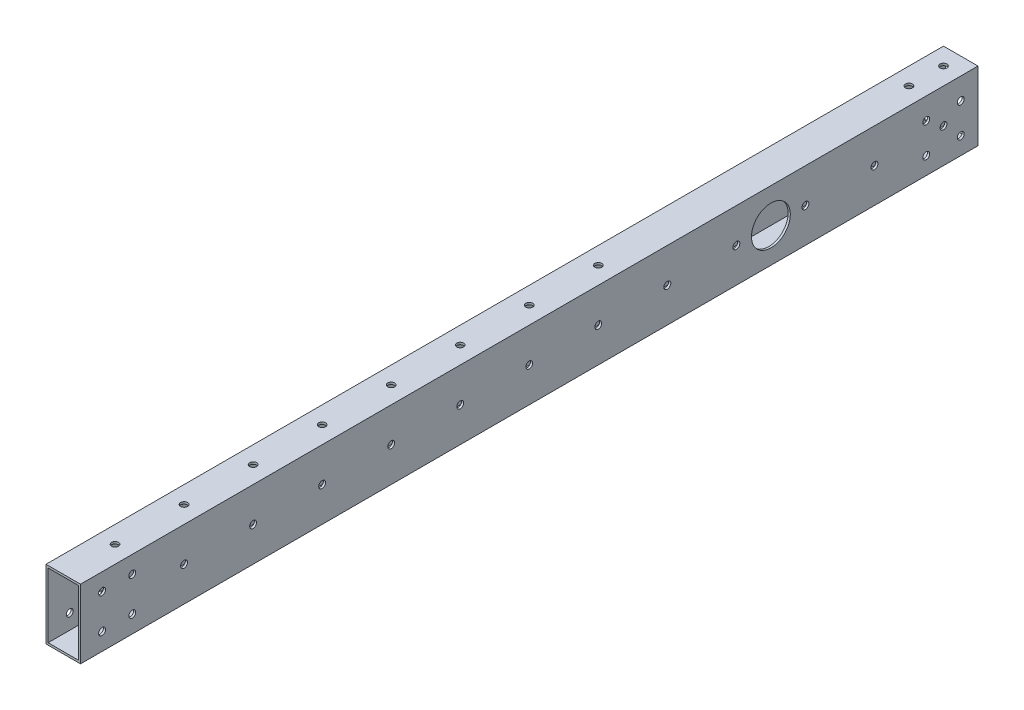
SolidWorks part; units mm, degrees
ref_plane "Front Plane" through (0, 0, 0) normal (0, 0, 1) x (1, 0, 0)
ref_plane "Top Plane" through (0, 0, 0) normal (0, 1, 0) x (1, 0, 0)
ref_plane "Right Plane" through (0, 0, 0) normal (1, 0, 0) x (0, 0, -1)
sketch "Sketch1" plane through (0, 0, 0) normal (0, 0, 1) x (1, 0, 0)
  line L0 (-11.1125, -23.8125) -> (11.1125, 23.8125) construction
  line L1 (-12.7, -25.4) -> (12.7, -25.4)
  line L2 (-12.7, -25.4) -> (-12.7, 25.4)
  line L3 (-12.7, 25.4) -> (12.7, 25.4)
  line L4 (12.7, -25.4) -> (12.7, 25.4)
  line L5 (-11.1125, -23.8125) -> (11.1125, -23.8125)
  line L6 (-11.1125, -23.8125) -> (-11.1125, 23.8125)
  line L7 (-11.1125, 23.8125) -> (11.1125, 23.8125)
  line L8 (11.1125, -23.8125) -> (11.1125, 23.8125)
  dimension "D1" = 25.4
  dimension "D2" = 50.8
  dimension "D3" = 1.5875
  dimension "D4" = 1.5875
  dimension "D5" = 1.5875
  dimension ".0625" = 1.5875
extrude "Boss-Extrude1" add sketch "Sketch1" along normal blind 660.4
sketch "Sketch2" plane through (12.7, 0, 0) normal (1, 0, 0) x (0, 0, -1)
  line L0 (-644.525, -12.7) -> (-660.4, 0) construction
  line L1 (-660.4, 25.4) -> (0, 25.4) construction
  line L2 (-660.4, -25.4) -> (0, -25.4) construction
  line L3 (0, -25.4) -> (0, 25.4) construction
  line L4 (-660.4, 0) -> (-644.525, 12.7) construction
  line L5 (-660.4, -25.4) -> (-660.4, 25.4) construction
  circle A0 centre (-38.1, 9.525) radius 2.54
  circle A1 centre (-38.1, -12.7) radius 2.54
  circle A2 centre (-12.7, 9.525) radius 2.54
  circle A3 centre (-12.7, -12.7) radius 2.54
  circle A4 centre (-152.4, 0) radius 14.2875
  circle A5 centre (-644.525, -12.7) radius 2.54
  circle A6 centre (-622.3, -12.7) radius 2.54
  circle A7 centre (-644.525, 12.7) radius 2.54
  circle A8 centre (-622.3, 12.7) radius 2.54
  circle A9 centre (-25.4, 0) radius 2.54
  circle A20 centre (-76.2, 0) radius 2.54
  circle A21 centre (-127, 0) radius 2.54
  circle A22 centre (-177.8, 0) radius 2.54
  circle A23 centre (-228.6, 0) radius 2.54
  circle A24 centre (-279.4, 0) radius 2.54
  circle A25 centre (-330.2, 0) radius 2.54
  circle A26 centre (-381, 0) radius 2.54
  circle A27 centre (-431.8, 0) radius 2.54
  circle A28 centre (-482.6, 0) radius 2.54
  circle A29 centre (-533.4, 0) radius 2.54
  circle A30 centre (-584.2, 0) radius 2.54
  point P28 (0, 0)
  dimension "D1" = 5.08
  dimension "D6" = 28.575
  dimension "D12" = 5.08
  dimension "D2" = 25.4
  dimension "D3" = 15.875
  dimension "D4" = 12.7
  dimension "D5" = 12.7
  dimension "D7" = 25.4
  dimension "D8" = 152.4
  dimension "D9" = 15.875
  dimension "D10" = 38.1
  dimension "D11" = 12.7
  dimension "D13" = 25.4
  dimension "D14" = 25.4
  dimension "D16" = 50.8
  dimension "D15" = 12
extrude "Cut-Extrude1" cut sketch "Sketch2" against normal through all
sketch "Sketch3" plane through (0, 25.4, 0) normal (0, 1, 0) x (1, 0, 0)
  line L0 (-12.7, -660.4) -> (-12.7, 0) construction
  line L1 (12.7, 0) -> (-12.7, 0) construction
  line L2 (12.7, -660.4) -> (-12.7, -660.4) construction
  circle A0 centre (0, -12.7) radius 2.54
  circle A1 centre (0, -38.1) radius 2.54
  circle A2 centre (0, -622.3) radius 2.54
  circle A3 centre (0, -571.5) radius 2.54
  circle A4 centre (0, -520.7) radius 2.54
  circle A5 centre (0, -469.9) radius 2.54
  circle A6 centre (0, -419.1) radius 2.54
  circle A7 centre (0, -368.3) radius 2.54
  circle A8 centre (0, -317.5) radius 2.54
  circle A9 centre (0, -266.7) radius 2.54
  dimension "D1" = 5.08
  dimension "D2" = 12.7
  dimension "D3" = 12.7
  dimension "D4" = 25.4
  dimension "D5" = 38.1
extrude "Cut-Extrude3" cut sketch "Sketch3" against normal through all
